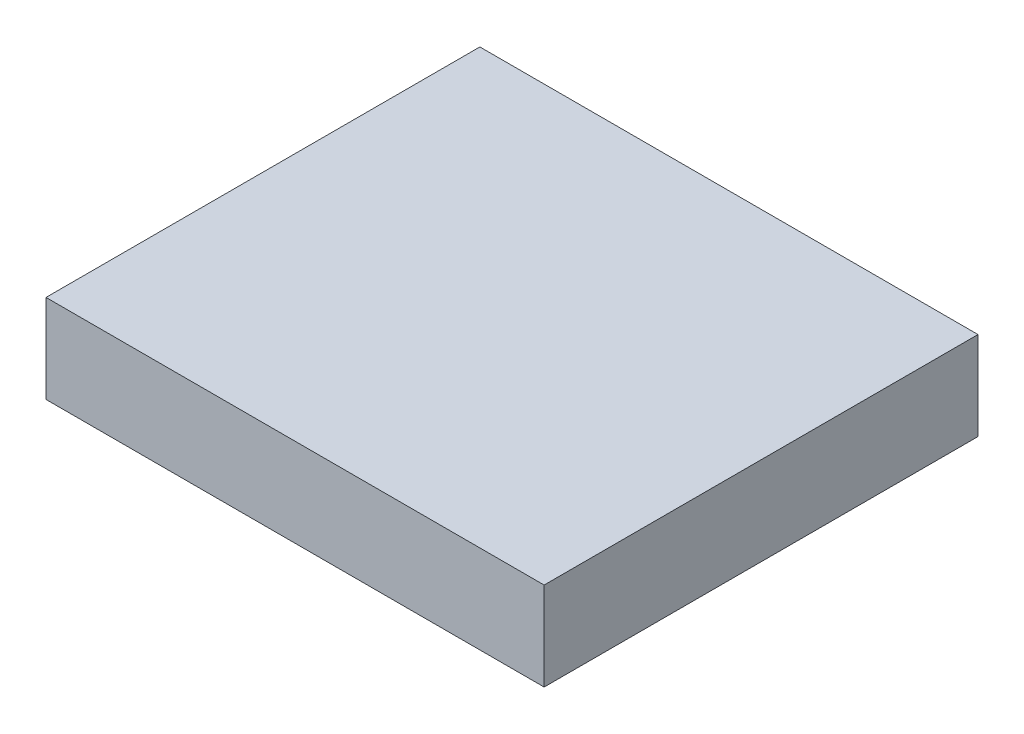
SolidWorks part; units mm, degrees
ref_plane "Front Plane" through (0, 0, 0) normal (0, 0, 1) x (1, 0, 0)
ref_plane "Top Plane" through (0, 0, 0) normal (0, 1, 0) x (1, 0, 0)
ref_plane "Right Plane" through (0, 0, 0) normal (1, 0, 0) x (0, 0, -1)
other "Configuration Table"
sketch "Sketch1" plane through (0, 0, 0) normal (0, 0, 1) x (1, 0, 0)
  line L1 (40, 1690) -> (660, 1690)
  line L2 (40, 1690) -> (40, 1800)
  line L3 (40, 1800) -> (660, 1800)
  line L4 (660, 1690) -> (660, 1800)
extrude "OVEN_plenum_kutusu_1" add sketch "Sketch1" against normal blind 540 from offset 40 separate body
